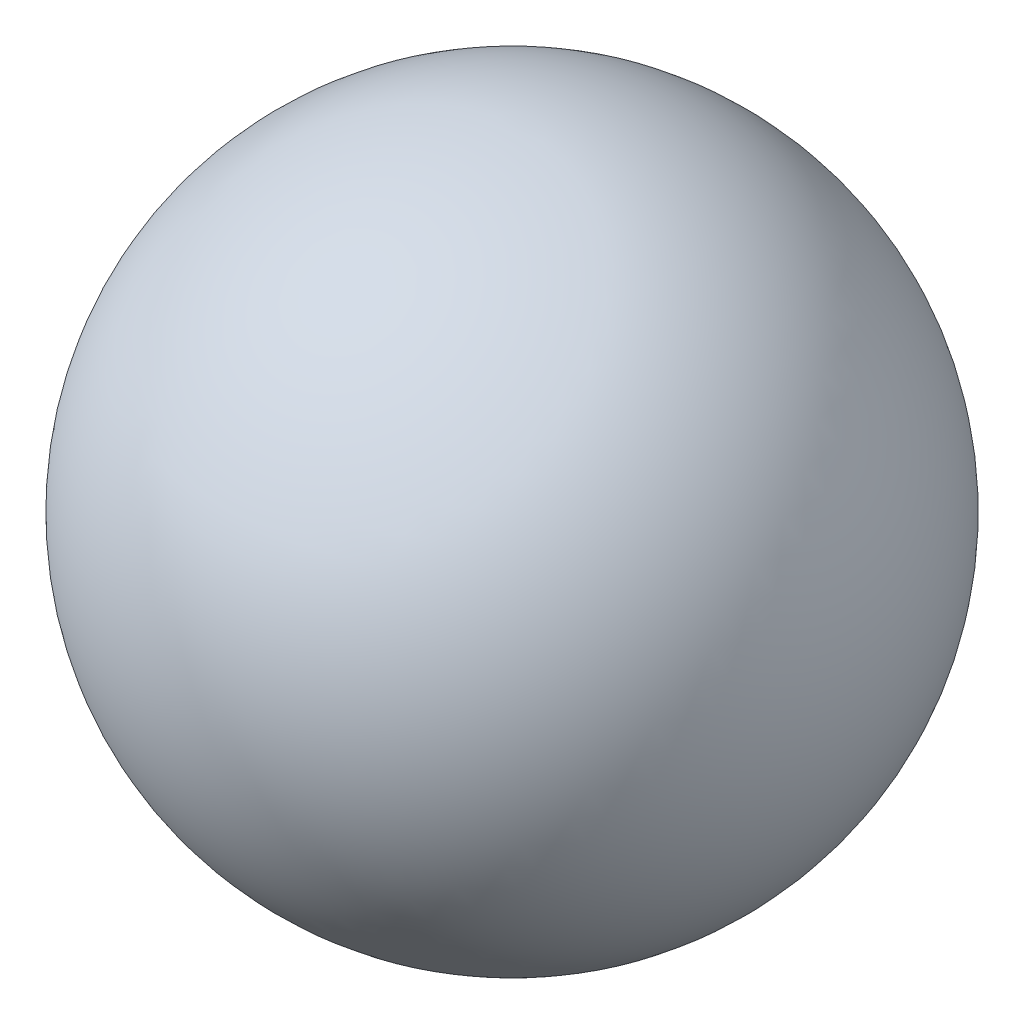
SolidWorks part; units mm, degrees
ref_plane "Front Plane" through (0, 0, 0) normal (0, 0, 1) x (1, 0, 0)
ref_plane "Top Plane" through (0, 0, 0) normal (0, 1, 0) x (1, 0, 0)
ref_plane "Right Plane" through (0, 0, 0) normal (1, 0, 0) x (0, 0, -1)
sketch "Sketch1" plane through (0, 0, 0) normal (0, 0, 1) x (1, 0, 0)
  line L0 (0, 8.5) -> (0, -8.5)
  arc A0 (0, -8.5) -> (0, 8.5) centre (0, 0) ccw
  dimension "D1" = 17
revolve "Revolve1" add sketch "Sketch1" angle 360 about L0
